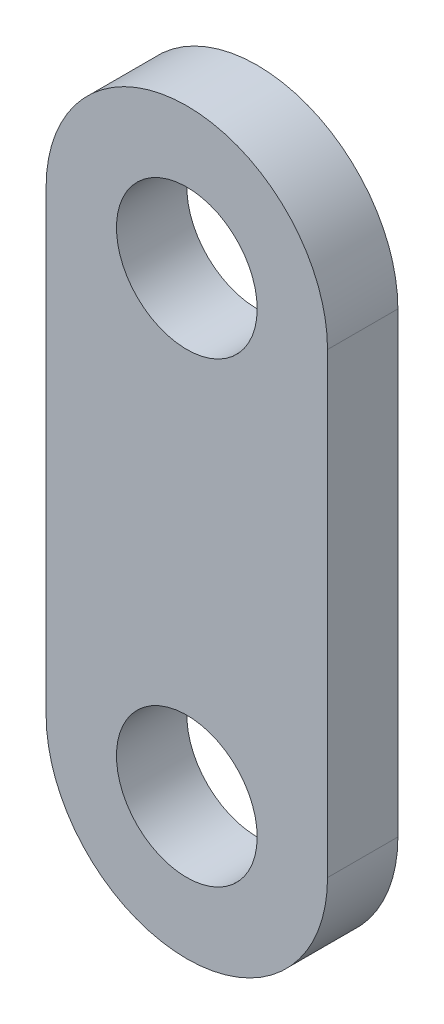
SolidWorks part; units mm, degrees
ref_plane "Front Plane" through (0, 0, 0) normal (0, 0, 1) x (1, 0, 0)
ref_plane "Top Plane" through (0, 0, 0) normal (0, 1, 0) x (1, 0, 0)
ref_plane "Right Plane" through (0, 0, 0) normal (1, 0, 0) x (0, 0, -1)
sketch "Sketch1" plane through (0, 0, 0) normal (0, 0, 1) x (1, 0, 0)
  line L0 (0, 10.3187) -> (0, -10.3187) construction
  line L1 (6.35, 10.3188) -> (6.35, -10.3187)
  line L2 (-6.35, 10.3187) -> (-6.35, -10.3188)
  arc A0 (6.35, 10.3188) -> (-6.35, 10.3187) centre (0, 10.3187) ccw
  arc A1 (-6.35, -10.3188) -> (6.35, -10.3187) centre (0, -10.3187) ccw
  point P2 (0, 0)
  point P8 (0, 16.6687)
  point P9 (0, -16.6687)
  dimension "D2" = 6.35
  dimension "D1" = 33.3375
extrude "Boss-Extrude1" add sketch "Sketch1" along normal blind 3.175
sketch "Sketch2" plane through (0, 0, 3.175) normal (0, 0, 1) x (1, 0, 0)
  line L0 (6.35, -10.3187) -> (6.35, 10.3188) construction
  line L1 (-6.35, 0) -> (6.35, 0) construction
  line L2 (-6.35, 10.3187) -> (-6.35, -10.3187) construction
  circle A0 centre (0, 10.3187) radius 3.175
  circle A1 centre (0, -10.3187) radius 3.175
  point P5 (0, 0)
  dimension "D1" = 6.35
  dimension "D3" = 6.35
  dimension "D2" = 6.35
  dimension "D4" = 20.6375
  dimension "D5" = 10.3187
  dimension "D6" = 6.35
extrude "Cut-Extrude1" cut sketch "Sketch2" against normal blind 3.175
